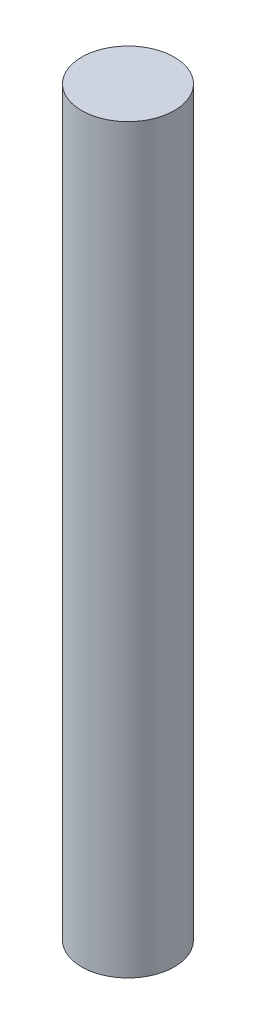
SolidWorks part; units mm, degrees
material "Alliage 1060"
ref_plane "Plan de face" through (0, 0, 0) normal (0, 0, 1) x (1, 0, 0)
ref_plane "Plan de dessus" through (0, 0, 0) normal (0, 1, 0) x (1, 0, 0)
ref_plane "Plan de droite" through (0, 0, 0) normal (1, 0, 0) x (0, 0, -1)
sketch "Esquisse1" plane through (0, 0, 0) normal (0, 1, 0) x (1, 0, 0)
  circle A0 centre (0, 0) radius 2.5
  dimension "D1" = 5
extrude "Boss.-Extru.1" add sketch "Esquisse1" along normal blind 40
